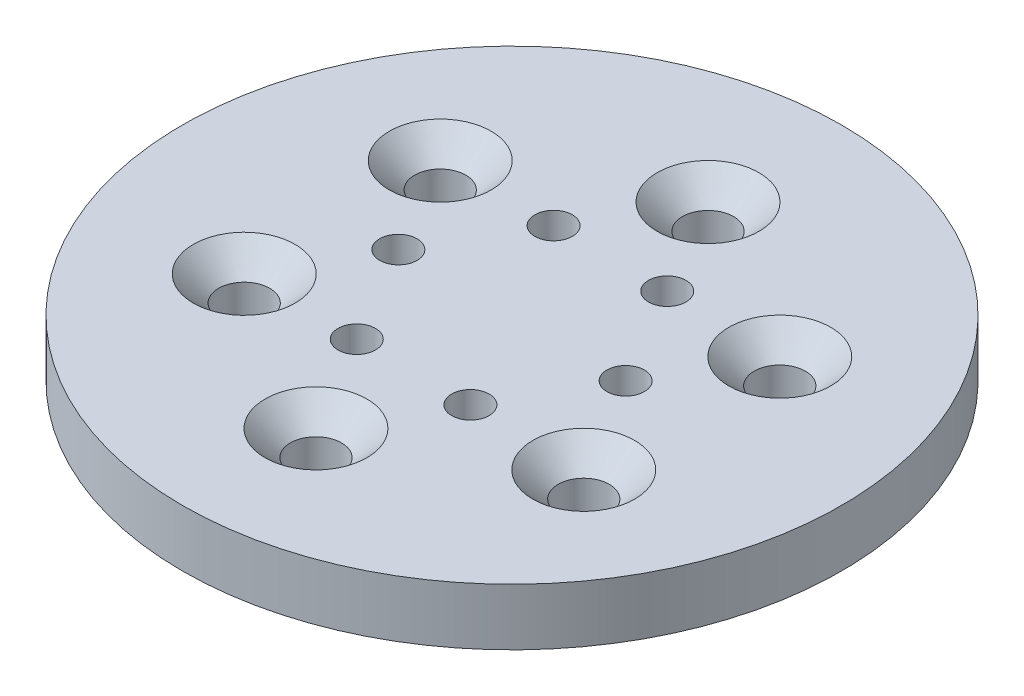
SolidWorks part; units mm, degrees
ref_plane "Ebene vorne" through (0, 0, 0) normal (0, 0, 1) x (1, 0, 0)
ref_plane "Ebene oben" through (0, 0, 0) normal (0, 1, 0) x (1, 0, 0)
ref_plane "Ebene rechts" through (0, 0, 0) normal (1, 0, 0) x (0, 0, -1)
sketch "Skizze1" plane through (0, 0, 0) normal (0, 1, 0) x (1, 0, 0)
  circle A0 centre (0, 0) radius 29
  dimension "D1" = 58
extrude "Aufsatz-Linear austragen1" add sketch "Skizze1" along normal blind 5
sketch "Skizze2" plane through (0, 5, 0) normal (0, 1, 0) x (1, 0, 0)
  circle A0 centre (0, 0) radius 17.25 construction
  circle A1 centre (0, 0) radius 17.25 construction
  circle A2 centre (0, 0) radius 17.25 construction
  circle A3 centre (0, 0) radius 17.25 construction
  circle A4 centre (0, 0) radius 17.25 construction
  circle A5 centre (0, 0) radius 17.25 construction
  point P3 (0, 17.25)
  point P13 (14.9389, 8.625)
  point P15 (14.9389, -8.625)
  point P17 (0, -17.25)
  point P19 (-14.9389, -8.625)
  point P21 (-14.9389, 8.625)
  dimension "D1" = 34.5
  dimension "D2" = 6
hole_wizard "Formsenkung für M4 Senkschraube mit Innensechskant1" positions "Skizze2" profile "Skizze3" countersink size "M4" standard "ISO" end condition through all
sketch "Skizze3" plane through (-14.9389, 5, -8.625) normal (1, 0, 0) x (0, 0, 1)
  line L0 (0, 0) -> (0, 5)
  line L1 (0, 5) -> (2.25, 5)
  line L2 (2.25, 5) -> (2.25, 2.23)
  line L3 (2.25, 2.23) -> (4.48, 0)
  line L5 (4.48, 0) -> (0, 0)
  line L6 (-2.25, 2.23) -> (-4.48, 0) construction
  line L11 (0, -6.35) -> (0, 107.95) construction
  dimension "Bohrerdurchmesser" = 4.5
  dimension "Bohrungstiefe" = 5
  dimension "Senkdurchmesser (Oben)" = 8.96
  dimension "Senkwinkel (Oben)" = 90
sketch "Skizze4" plane through (0, 5, 0) normal (0, 1, 0) x (1, 0, 0)
  line L0 (-5, 8.6603) -> (0, 0) construction
  line L1 (0, 0) -> (0, 10) construction
  circle A0 centre (0, 0) radius 10 construction
  point P8 (-5, 8.6603)
  point P11 (-5, 8.6603)
  point P18 (5, 8.6603)
  point P19 (10, 0)
  point P20 (5, -8.6603)
  point P21 (-5, -8.6603)
  point P22 (-10, 0)
  dimension "D1" = 20
  dimension "D2" = 30
  dimension "D3" = 6
hole_wizard "M4 Gewindebohrung1" positions "Skizze4" profile "Skizze5" tap size "M4" standard "ISO" end condition through all
sketch "Skizze5" plane through (-10, 5, 0) normal (1, 0, 0) x (0, 0, 1)
  line L0 (0, 0) -> (0, 5)
  line L1 (0, 5) -> (1.65, 5)
  line L2 (1.65, 5) -> (1.65, 0)
  line L5 (1.65, 0) -> (0, 0)
  line L11 (0, -6.35) -> (0, 107.95) construction
  dimension "Bohrerdurchmesser" = 3.3
  dimension "Bohrungstiefe" = 5
cosmetic thread "Bohrungsgewinde1" parameters "D2"=4
cosmetic thread "Bohrungsgewinde2" parameters "D2"=4
cosmetic thread "Bohrungsgewinde3" parameters "D2"=4
cosmetic thread "Bohrungsgewinde4" parameters "D2"=4
cosmetic thread "Bohrungsgewinde5" parameters "D2"=4
cosmetic thread "Bohrungsgewinde6" parameters "D2"=4
cosmetic thread "Bohrungsgewinde7" parameters "D2"=4
